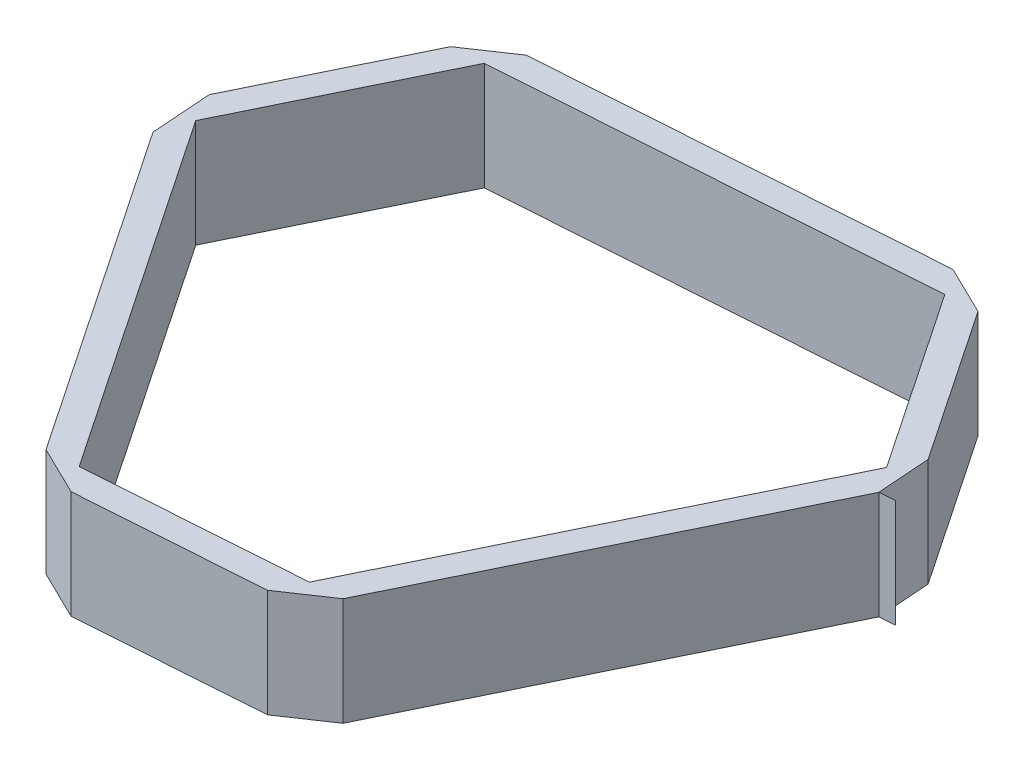
SolidWorks part; units mm, degrees
ref_plane "Front Plane" through (0, 0, 0) normal (0, 0, 1) x (1, 0, 0)
ref_plane "Top Plane" through (0, 0, 0) normal (0, 1, 0) x (1, 0, 0)
ref_plane "Right Plane" through (0, 0, 0) normal (1, 0, 0) x (0, 0, -1)
sketch "Sketch1" plane through (0, 0, 0) normal (0, 1, 0) x (1, 0, 0)
  line L0 (28.4005, -42.1195) -> (-28.4005, 42.1195)
  line L1 (-28.4005, 42.1195) -> (-6.1242, 87.7748)
  line L11 (-6.1242, 87.7748) -> (95.2294, 94.8464)
  line L12 (79.0773, -38.5837) -> (123.6299, 52.7269)
  line L13 (123.6299, 52.7269) -> (95.2294, 94.8464)
  line L14 (79.0773, -38.5837) -> (28.4005, -42.1195)
  line L15 (83.1766, -44.6631) -> (25.1852, -48.7093)
  line L16 (25.1852, -48.7093) -> (-35.7151, 41.6091)
  line L17 (-35.7151, 41.6091) -> (-10.2235, 93.8542)
  line L18 (-10.2235, 93.8542) -> (98.4447, 101.4362)
  line L19 (130.9445, 53.2373) -> (98.4447, 101.4362)
  line L20 (83.1766, -44.6631) -> (130.9445, 53.2373)
  point P4 (0, 0)
  dimension "D1" = 101.6
  dimension "D2" = 6.35
  dimension "D3" = 120
  dimension "D5" = 50.8
  dimension "D6" = 101.6
extrude "Boss-Extrude1" add sketch "Sketch1" along normal blind 25.4
sketch "Sketch2" plane through (0, 25.4, 0) normal (0, 1, 0) x (1, 0, 0)
  line L0 (123.1938, 58.9769) -> (124.0638, 46.5073)
  line L1 (130.5419, 59.4896) -> (131.412, 47.02)
  line L15 (123.1938, 58.9769) -> (130.5419, 59.4896)
  line L16 (131.412, 47.02) -> (124.0638, 46.5073)
  point P4 (123.6299, 52.7269)
  point P7 (123.6299, 52.7269)
  point P10 (123.6299, 52.7269)
  point P20 (48.6354, 32.7941)
  dimension "D1" = 12.5
extrude "Boss-Extrude2" add sketch "Sketch2" against normal up to surface (25.4 mm away) up to face at (48.6354, 0, -32.7941)
sketch "Sketch3" plane through (134.0401, 0, -9.3522) normal (0.9976, 0, -0.0696) x (-0.0696, 0, -0.9976)
  circle A0 centre (41.0093, 23.4) radius 2
  circle A1 centre (47.0093, 23.4) radius 2
  point P3 (44.0093, 25.4)
extrude "Boss-Extrude3" add sketch "Sketch3" along normal blind 5 contours A0 | A1
sketch "Sketch4" plane through (0, 25.4, 0) normal (0, 1, 0) x (1, 0, 0)
  line L0 (126.8999, 59.2355) -> (127.7875, 46.7671)
  line L1 (126.8999, 59.2355) -> (138.4929, 60.0607)
  line L2 (127.7875, 46.7671) -> (139.3804, 47.5923)
  line L3 (138.4929, 60.0607) -> (139.3804, 47.5923)
extrude "Cut-Extrude1" cut sketch "Sketch4" against normal up to surface (25.4 mm away) up to face at (75.2788, 0, -39.5599)
sketch "Sketch5" plane through (0, 25.4, 0) normal (0, 1, 0) x (1, 0, 0)
  line L0 (126.8999, 59.2355) -> (123.6299, 52.7269)
  line L1 (123.6299, 52.7269) -> (127.7875, 46.7671)
  line L2 (126.8999, 59.2355) -> (127.7875, 46.7671)
  line L3 (102.5813, 95.3014) -> (95.2294, 94.8464)
  line L4 (95.2294, 94.8464) -> (91.0634, 100.9212)
  line L5 (102.5813, 95.3014) -> (91.0634, 100.9212)
  line L6 (126.8999, 59.2355) -> (98.4447, 101.4362) construction
  line L7 (98.4447, 101.4362) -> (-10.2235, 93.8542) construction
  line L8 (91.0634, 100.9212) -> (98.4447, 101.4362)
  line L9 (-13.4681, 87.2044) -> (-6.1242, 87.7748)
  line L10 (-6.1242, 87.7748) -> (-2.8422, 94.3692)
  line L11 (-13.4681, 87.2044) -> (-2.8422, 94.3692)
  line L12 (-10.2235, 93.8542) -> (-35.7151, 41.6091) construction
  line L13 (-32.0892, 49.0403) -> (-28.4005, 42.1195)
  line L14 (-28.4005, 42.1195) -> (-31.0924, 34.7535)
  line L15 (-32.0892, 49.0403) -> (-31.0924, 34.7535)
  line L16 (-35.7151, 41.6091) -> (25.1852, -48.7093) construction
  line L17 (21.0486, -42.5744) -> (28.4005, -42.1195)
  line L18 (28.4005, -42.1195) -> (32.5665, -48.1943)
  line L19 (21.0486, -42.5744) -> (32.5665, -48.1943)
  line L20 (25.1852, -48.7093) -> (83.1766, -44.6631) construction
  line L27 (86.4212, -38.0132) -> (79.0773, -38.5837)
  line L28 (79.0773, -38.5837) -> (75.7953, -45.1781)
  line L29 (86.4212, -38.0132) -> (75.7953, -45.1781)
  line L30 (83.1766, -44.6631) -> (127.7875, 46.7671) construction
  line L31 (-32.0892, 49.0403) -> (-35.7151, 41.6091)
  line L32 (-35.7151, 41.6091) -> (-31.0924, 34.7535)
  line L33 (-32.0892, 49.0403) -> (-35.7151, 41.6091)
  line L34 (21.0486, -42.5744) -> (25.1852, -48.7093)
  line L35 (25.1852, -48.7093) -> (32.5665, -48.1943)
  line L36 (75.7953, -45.1781) -> (86.4212, -38.0132)
  line L37 (83.1766, -44.6631) -> (75.7953, -45.1781)
  line L38 (86.4212, -38.0132) -> (83.1766, -44.6631)
  line L39 (98.4447, 101.4362) -> (102.5813, 95.3014)
  line L40 (91.0634, 100.9212) -> (102.5813, 95.3014)
  line L41 (-13.4681, 87.2044) -> (-10.2235, 93.8542)
  line L42 (-10.2235, 93.8542) -> (-2.8422, 94.3692)
  line L43 (-13.4681, 87.2044) -> (-2.8422, 94.3692)
  line M19 (-10.2235, 93.8542) -> (-35.7151, 41.6091)
  line M20 (-35.7151, 41.6091) -> (25.1852, -48.7093)
  dimension "D1" = 7.366
  dimension "D2" = 7.366
  dimension "D3" = 7.366
extrude "Cut-Extrude7" cut sketch "Sketch5" against normal up to surface (25.4 mm away) contours L15 M19 M20 up to face at (59.365, 0, -35.6471)
sketch "Sketch7" plane through (0, 25.4, 0) normal (0, 1, 0) x (1, 0, 0)
  line L0 (75.7953, -45.1781) -> (86.4212, -38.0132)
  line L1 (86.4212, -38.0132) -> (83.1766, -44.6631)
  line L2 (83.1766, -44.6631) -> (75.7953, -45.1781)
  line L3 (21.0486, -42.5744) -> (25.1852, -48.7093)
  line L4 (25.1852, -48.7093) -> (32.5665, -48.1943)
  line L5 (32.5665, -48.1943) -> (21.0486, -42.5744)
  line L6 (-10.2235, 93.8542) -> (-2.8422, 94.3692)
  line L7 (-2.8422, 94.3692) -> (-13.4681, 87.2044)
  line L8 (-13.4681, 87.2044) -> (-10.2235, 93.8542)
  line L9 (91.0634, 100.9212) -> (98.4447, 101.4362)
  line L10 (98.4447, 101.4362) -> (102.5813, 95.3014)
  line L11 (102.5813, 95.3014) -> (91.0634, 100.9212)
extrude "Cut-Extrude8" cut sketch "Sketch7" against normal up to surface (25.4 mm away) up to face at (48.6354, 0, -32.7941)
